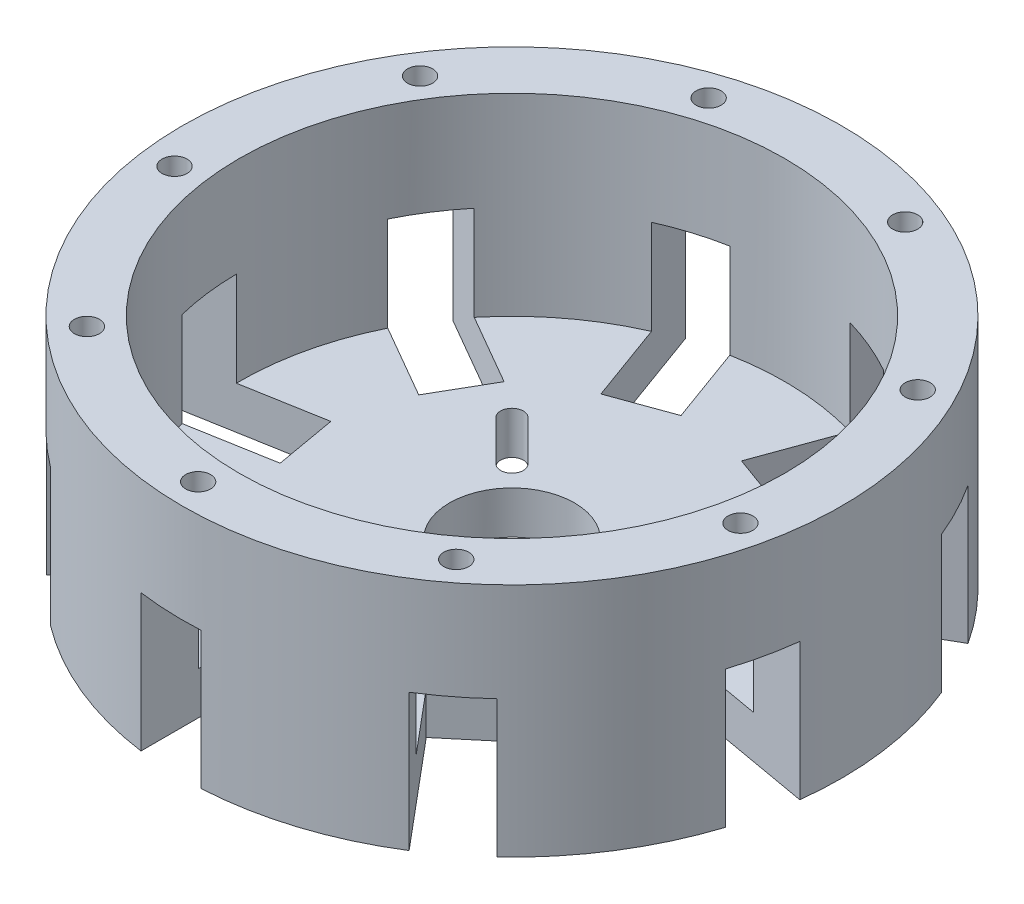
SolidWorks part; units mm, degrees
ref_plane "Front Plane" through (0, 0, 0) normal (0, 0, 1) x (1, 0, 0)
ref_plane "Top Plane" through (0, 0, 0) normal (0, 1, 0) x (1, 0, 0)
ref_plane "Right Plane" through (0, 0, 0) normal (1, 0, 0) x (0, 0, -1)
sketch "Sketch2" plane through (0, 0, 0) normal (0, 1, 0) x (1, 0, 0)
  circle A0 centre (0, 0) radius 58
  dimension "D1" = 116
extrude "Boss-Extrude1" add sketch "Sketch2" along normal blind 41.5
sketch "Sketch3" plane through (0, 41.5, 0) normal (0, 1, 0) x (1, 0, 0)
  circle A0 centre (0, 0) radius 48
  circle A1 centre (0, 0) radius 58 construction
  dimension "D1" = 96
  dimension "D2" = 10
extrude "Cut-Extrude1" cut sketch "Sketch3" against normal offset from surface (34 mm away) 34 up to face at (0, 41.5, 58)
sketch "Sketch4" plane through (0, 7.5, 0) normal (0, 1, 0) x (1, 0, 0)
  circle A0 centre (0, 0) radius 3.175
  dimension "D1" = 6.35
extrude "Cut-Extrude2" cut sketch "Sketch4" against normal through all
sketch "Sketch5" plane through (0, 0, 0) normal (0, -1, 0) x (1, 0, 0)
  line L0 (0, 0) -> (2.2451, 2.2451) construction
  line L1 (0, 0) -> (-2.2451, 2.2451) construction
  line L2 (0, 0) -> (-2.2451, -2.2451) construction
  line L3 (0, 0) -> (2.2451, -2.2451) construction
  line L4 (2.2451, -2.2451) -> (11.4375, -11.4375) construction
  line L5 (0, 0) -> (0, -3.175) construction
  line L6 (11.4375, -11.4375) -> (18.5085, -18.5085) construction
  line L7 (2.2451, 2.2451) -> (11.4375, 11.4375) construction
  line L8 (12.8517, -10.0232) -> (19.9227, -17.0943)
  line L9 (10.0232, -12.8517) -> (17.0943, -19.9227)
  line L10 (11.4375, 11.4375) -> (18.5085, 18.5085) construction
  line L11 (10.0232, 12.8517) -> (17.0943, 19.9227)
  line L12 (12.8517, 10.0232) -> (19.9227, 17.0943)
  line L13 (-11.4375, 11.4375) -> (-18.5085, 18.5085) construction
  line L14 (-10.0232, 12.8517) -> (-17.0943, 19.9227)
  line L15 (-12.8517, 10.0232) -> (-19.9227, 17.0943)
  line L16 (-11.4375, -11.4375) -> (-18.5085, -18.5085) construction
  line L17 (-12.8517, -10.0232) -> (-19.9227, -17.0943)
  line L18 (-10.0232, -12.8517) -> (-17.0943, -19.9227)
  circle A0 centre (0, 0) radius 3.175 construction
  arc A1 (12.8517, -10.0232) -> (10.0232, -12.8517) centre (11.4375, -11.4375) ccw
  arc A2 (17.0943, -19.9227) -> (19.9227, -17.0943) centre (18.5085, -18.5085) ccw
  arc A3 (10.0232, 12.8517) -> (12.8517, 10.0232) centre (11.4375, 11.4375) ccw
  arc A4 (19.9227, 17.0943) -> (17.0943, 19.9227) centre (18.5085, 18.5085) ccw
  arc A5 (-10.0232, 12.8517) -> (-12.8517, 10.0232) centre (-11.4375, 11.4375) cw
  arc A6 (-19.9227, 17.0943) -> (-17.0943, 19.9227) centre (-18.5085, 18.5085) cw
  arc A7 (-12.8517, -10.0232) -> (-10.0232, -12.8517) centre (-11.4375, -11.4375) cw
  arc A8 (-17.0943, -19.9227) -> (-19.9227, -17.0943) centre (-18.5085, -18.5085) cw
  point P8 (14.973, -14.973)
  point P18 (14.973, 14.973)
  point P26 (-14.973, 14.973)
  point P33 (-14.973, -14.973)
  dimension "D1" = 13
  dimension "D2" = 13
extrude "Cut-Extrude3" cut sketch "Sketch5" against normal through all
ref_plane "Plane1" through (0, 0, 58) normal (0, 0, 1) x (1, 0, 0)
sketch "Sketch6" plane through (0, 0, 58) normal (0, 0, 1) x (1, 0, 0)
  line L1 (-7.825, 24.13) -> (3.175, 24.13)
  line L2 (-7.825, 24.13) -> (-7.825, -1.27)
  line L3 (-7.825, -1.27) -> (3.175, -1.27)
  line L4 (3.175, 24.13) -> (3.175, -1.27)
  line L8 (-58, 0) -> (58, 0) construction
  dimension "D1" = 1.27
  dimension "D2" = 25.4
  dimension "D3" = 11
extrude "Cut-Extrude4" cut sketch "Sketch6" against normal blind 25
pattern_circular "CirPattern1" count 9 every 40 about axis through (0, 0, 0) along (0, 1, 0) of "Cut-Extrude4"
sketch "Sketch7" plane through (0, 24.13, 0) normal (0, -1, 0) x (1, 0, 0)
  line L2 (-2.3355, 52.904) -> (3.175, 52.904) construction
  line L3 (3.175, 47.8949) -> (3.175, 57.913) construction
  line L4 (-2.3355, 52.904) -> (-2.3355, 57.953) construction
  circle A0 centre (-2.3355, 52.904) radius 2.2
  arc A1 (3.175, 57.913) -> (-7.825, 57.4697) centre (0, 0) ccw construction
  dimension "D1" = 4.4
extrude "Cut-Extrude5" cut sketch "Sketch7" against normal through all
pattern_circular "CirPattern2" count 9 over 360 about axis through (0, 0, 0) along (0, 1, 0) of "Cut-Extrude5"
sketch "Sketch8" plane through (0, 0, 0) normal (0, -1, 0) x (1, 0, 0)
  circle A0 centre (0, 0) radius 11
  arc A1 (-12.8517, 10.0232) -> (-10.0232, 12.8517) centre (-11.4375, 11.4375) ccw construction
  arc A2 (-17.0943, 19.9227) -> (-19.9227, 17.0943) centre (-18.5085, 18.5085) ccw construction
  point P11 (-19.9227, 19.9227)
  dimension "D1" = 22
  dimension "D2" = 16.175
  dimension "D3" = 16.2982
  dimension "D4" = 28.175
extrude "Cut-Extrude6" cut sketch "Sketch8" against normal through all
